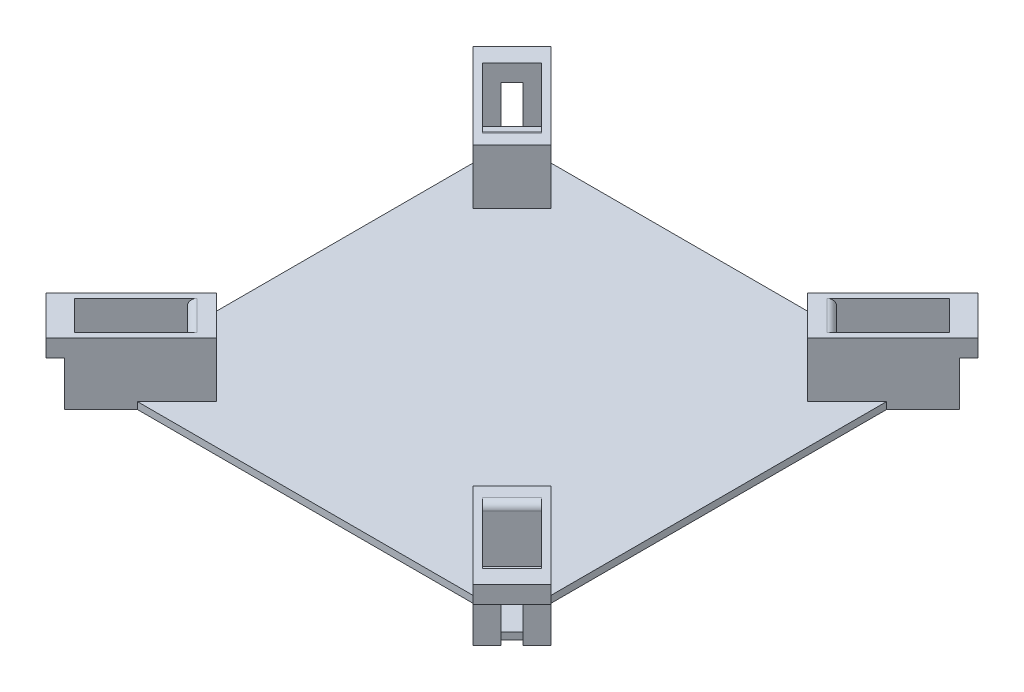
SolidWorks part; units mm, degrees
ref_plane "Front Plane" through (0, 0, 0) normal (0, 0, 1) x (1, 0, 0)
ref_plane "Top Plane" through (0, 0, 0) normal (0, 1, 0) x (1, 0, 0)
ref_plane "Right Plane" through (0, 0, 0) normal (1, 0, 0) x (0, 0, -1)
sketch "Sketch1" plane through (0, 0, 0) normal (0, 1, 0) x (1, 0, 0)
  line L0 (0, -1141.5472) -> (0, 55935.811) construction
  line L1 (-1141.5472, 0) -> (55935.811, 0) construction
  line L2 (-986.1745, 70.6066) -> (49013.8255, 70.6066) construction
  line L3 (60, -60) -> (-60, -60)
  line L4 (60, -60) -> (60, 60)
  line L5 (60, 60) -> (-60, 60)
  line L6 (-60, -60) -> (-60, 60)
  line L7 (60, -60) -> (-60, 60) construction
  line L8 (60, 60) -> (-60, -60) construction
  line L9 (-70.6066, -1008.0553) -> (-70.6066, 48991.9447) construction
  line L10 (-60, 48.6863) -> (-70.6066, 59.2929)
  line L11 (-70.6066, 59.2929) -> (-59.2929, 70.6066)
  line L12 (-59.2929, 70.6066) -> (-48.6863, 60)
  line L13 (-757.319, 757.319) -> (34598.0201, -34598.0201) construction
  line L14 (757.319, 757.319) -> (-34598.0201, -34598.0201) construction
  line L15 (60, 48.6863) -> (70.6066, 59.2929)
  line L16 (59.2929, 70.6066) -> (48.6863, 60)
  line L17 (70.6066, 59.2929) -> (59.2929, 70.6066)
  line L18 (-986.1745, -70.6066) -> (49013.8255, -70.6066) construction
  line L19 (60, -48.6863) -> (70.6066, -59.2929)
  line L20 (59.2929, -70.6066) -> (48.6863, -60)
  line L21 (70.6066, -59.2929) -> (59.2929, -70.6066)
  line L22 (757.319, -757.319) -> (-34598.0201, 34598.0201) construction
  line L23 (-757.319, -757.319) -> (34598.0201, 34598.0201) construction
  line L24 (-59.2929, -70.6066) -> (-48.6863, -60)
  line L25 (-70.6066, -59.2929) -> (-59.2929, -70.6066)
  line L26 (-60, -48.6863) -> (-70.6066, -59.2929)
  point P3 (0, 0)
  point P16 (-64.9497, 64.9497)
  dimension "D1" = 120
  dimension "D2" = 120
  dimension "D3" = 15
  dimension "D4" = 15
  dimension "D5" = 16
extrude "Boss-Extrude1" add sketch "Sketch1" along normal blind 2 contours L6 L26 L25 L24 L3 | L12 L11 L10 L6 L5 | L6 L3 L4 L5 | L15 L17 L16 L5 L4 | L21 L19 L4 L3 L20
sketch "Sketch2" plane through (0, 0, 0) normal (0, 1, 0) x (1, 0, 0)
  line L0 (59.2929, -70.6066) -> (70.6066, -59.2929)
  line L1 (59.2929, -70.6066) -> (57.8787, -69.1924)
  line L2 (70.6066, -59.2929) -> (69.1924, -57.8787)
  line L3 (59.2222, -67.8489) -> (67.8489, -59.2222)
  line L4 (57.8787, -69.1924) -> (41.4738, -52.7875)
  line L7 (59.2222, -67.8489) -> (42.8173, -51.444)
  line L8 (-707.1068, 707.1068) -> (34648.2323, -34648.2323) construction
  line L10 (69.1924, -57.8787) -> (52.7875, -41.4738)
  line L11 (67.8489, -59.2222) -> (51.444, -42.8173)
  line L12 (42.8173, -51.444) -> (51.444, -42.8173)
  line L13 (41.4738, -52.7875) -> (37.2312, -48.5449)
  line L14 (52.7875, -41.4738) -> (48.5449, -37.2312)
  line L15 (37.2312, -48.5449) -> (48.5449, -37.2312)
  dimension "D1" = 2
  dimension "D2" = 1.9
  dimension "D3" = 23.2
  dimension "D4" = 6
  dimension "D5" = 23.2
  dimension "D6" = 1.9
extrude "Boss-Extrude2" add sketch "Sketch2" along normal blind 13
mirror "Mirror1" about plane through (0, 0, 0) normal (1, 0, 0) of "Boss-Extrude2"
mirror "Mirror2" about plane through (0, 0, 0) normal (0, 0, 1) of "Boss-Extrude2", "Mirror1"
sketch "Sketch3" plane through (0, 13, 0) normal (0, 1, 0) x (1, 0, 0)
  line L0 (61.9445, -65.1265) -> (63.3588, -66.5407)
  line L1 (61.9445, -65.1265) -> (65.1265, -61.9445)
  line L2 (63.3588, -66.5407) -> (66.5407, -63.3588)
  line L3 (65.1265, -61.9445) -> (66.5407, -63.3588)
  line L4 (59.2222, -67.8489) -> (67.8489, -59.2222) construction
  line L5 (59.2929, -70.6066) -> (70.6066, -59.2929) construction
  line L6 (67.8489, -59.2222) -> (59.2222, -67.8489) construction
  line L7 (37.2312, -48.5449) -> (59.2929, -70.6066) construction
  line L8 (-707.1068, 707.1068) -> (34648.2323, -34648.2323) construction
  line L9 (70.6066, -59.2929) -> (48.5449, -37.2312) construction
  point P13 (64.9497, -64.9497)
  dimension "D1" = 4.5
extrude "Cut-Extrude1" cut sketch "Sketch3" against normal blind 16.5
mirror "Mirror3" about plane through (0, 0, 0) normal (1, 0, 0) of "Cut-Extrude1"
mirror "Mirror4" about plane through (0, 0, 0) normal (0, 0, 1) of "Mirror3", "Cut-Extrude1"
sketch "Sketch4" plane through (0, 13, 0) normal (0, 1, 0) x (1, 0, 0)
  line L0 (37.2312, 48.5449) -> (48.5449, 37.2312)
  line L1 (37.2312, 48.5449) -> (61.9799, 73.2936)
  line L2 (48.5449, 37.2312) -> (73.2936, 61.9799)
  line L3 (61.9799, 73.2936) -> (73.2936, 61.9799)
  dimension "D1" = 35
extrude "Boss-Extrude3" add sketch "Sketch4" along normal blind 5
sketch "Sketch7" plane through (0, 18, 0) normal (0, 1, 0) x (1, 0, 0)
  line L0 (42.8173, 51.444) -> (51.444, 42.8173)
  line L1 (42.8173, 51.444) -> (59.2222, 67.8489)
  line L2 (51.444, 42.8173) -> (67.8489, 59.2222)
  line L3 (59.2222, 67.8489) -> (67.8489, 59.2222)
  line L4 (61.9799, 73.2936) -> (37.2312, 48.5449) construction
  line L5 (37.2312, 48.5449) -> (48.5449, 37.2312) construction
  line L6 (-707.1068, -707.1068) -> (34648.2323, 34648.2323) construction
  line L7 (73.2936, 61.9799) -> (61.9799, 73.2936) construction
  point P9 (63.5355, 63.5355)
  point P14 (67.6368, 67.6368)
  dimension "D1" = 12.2
  dimension "D2" = 23.2
  dimension "D3" = 6
extrude "Cut-Extrude2" cut sketch "Sketch7" against normal blind 6
mirror "Mirror5" about plane through (0, 0, 0) normal (0, 0, 1) of "Cut-Extrude2", "Boss-Extrude3"
mirror "Mirror6" about plane through (0, 0, 0) normal (1, 0, 0) of "Mirror5", "Boss-Extrude3", "Cut-Extrude2"
fillet "Fillet1" radius 2 1 edges at (-47.1307, 18, -47.1307)
fillet "Fillet2" radius 2 1 edges at (-47.1307, 18, 47.1307)
fillet "Fillet3" radius 2 1 edges at (47.1307, 18, -47.1307)
fillet "Fillet4" radius 2 1 edges at (47.1307, 18, 47.1307)
